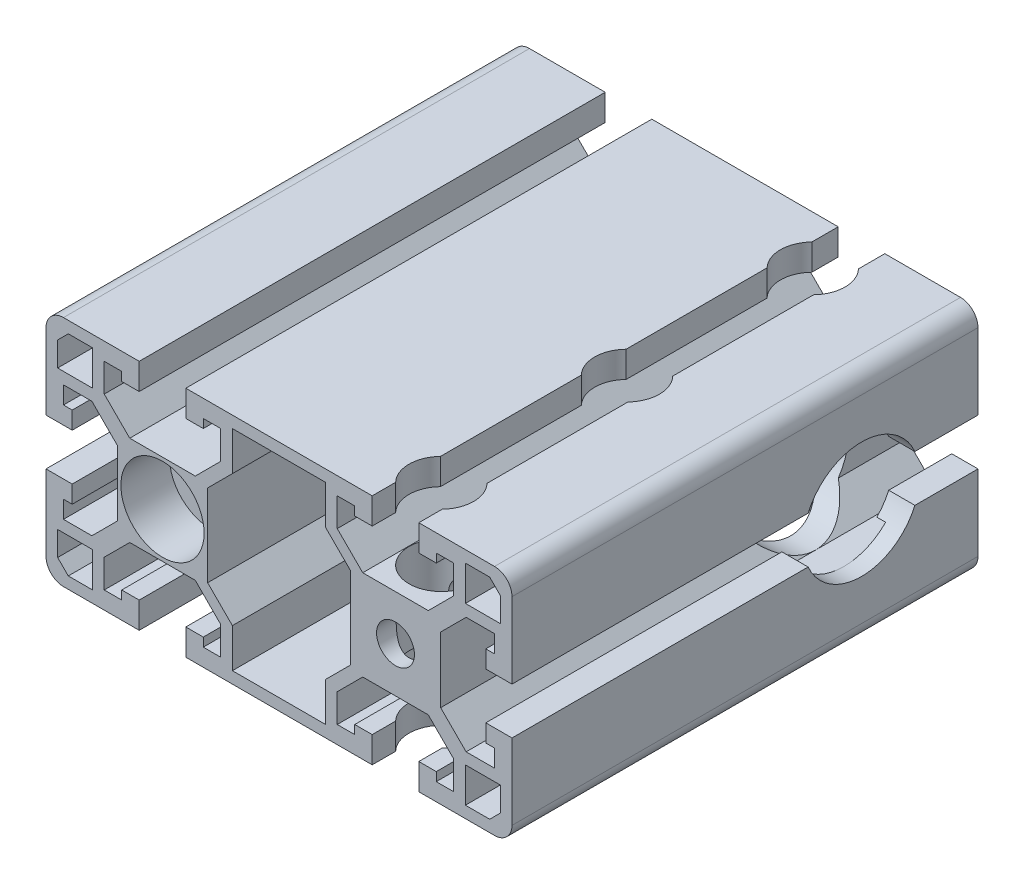
SolidWorks part; units mm, degrees
material "6061 Aluminum Alloy"
ref_plane "Front Plane" through (0, 0, 0) normal (0, 0, 1) x (1, 0, 0)
ref_plane "Top Plane" through (0, 0, 0) normal (0, 1, 0) x (1, 0, 0)
ref_plane "Right Plane" through (0, 0, 0) normal (1, 0, 0) x (0, 0, -1)
ref_plane "Plane1"
sketch "Sketch1" plane through (0, 0, 0) normal (0, 0, 1) x (1, 0, 0)
  line L0 (-24, 24) -> (-24, 37)
  line L1 (-21, 40) -> (-8, 40)
  line L2 (-8, 40) -> (-8, 35.5)
  line L3 (-8, 35.5) -> (-11, 35.5)
  line L4 (-11, 35.5) -> (-11, 37)
  line L5 (-11, 37) -> (-14, 37)
  line L6 (-14, 37) -> (-14, 32.125)
  line L7 (-14, 32.125) -> (-9.625, 27.75)
  line L8 (-9.625, 27.75) -> (1.625, 27.75)
  line L9 (1.625, 27.75) -> (6, 32.125)
  line L10 (6, 32.125) -> (6, 37)
  line L11 (6, 37) -> (3, 37)
  line L12 (3, 37) -> (3, 35.5)
  line L13 (3, 35.5) -> (0, 35.5)
  line L14 (0, 35.5) -> (0, 40)
  line L15 (0, 40) -> (32, 40)
  line L16 (32, 40) -> (32, 35.5)
  line L17 (32, 35.5) -> (29, 35.5)
  line L18 (29, 35.5) -> (29, 37)
  line L19 (29, 37) -> (26, 37)
  line L20 (26, 37) -> (26, 32.125)
  line L21 (26, 32.125) -> (30.375, 27.75)
  line L22 (30.375, 27.75) -> (41.625, 27.75)
  line L23 (41.625, 27.75) -> (46, 32.125)
  line L24 (46, 32.125) -> (46, 37)
  line L25 (46, 37) -> (43, 37)
  line L26 (43, 37) -> (43, 35.5)
  line L27 (43, 35.5) -> (40, 35.5)
  line L28 (40, 35.5) -> (40, 40)
  line L29 (40, 40) -> (53, 40)
  line L30 (56, 37) -> (56, 24)
  line L31 (56, 24) -> (51.5, 24)
  line L32 (51.5, 24) -> (51.5, 27)
  line L33 (51.5, 27) -> (53, 27)
  line L34 (53, 27) -> (53, 30)
  line L35 (53, 30) -> (48.125, 30)
  line L36 (48.125, 30) -> (43.75, 25.625)
  line L37 (43.75, 25.625) -> (43.75, 14.375)
  line L38 (43.75, 14.375) -> (48.125, 10)
  line L39 (48.125, 10) -> (53, 10)
  line L40 (53, 10) -> (53, 13)
  line L41 (53, 13) -> (51.5, 13)
  line L42 (51.5, 13) -> (51.5, 16)
  line L43 (51.5, 16) -> (56, 16)
  line L44 (56, 16) -> (56, 3)
  line L45 (53, 0) -> (40, 0)
  line L46 (40, 0) -> (40, 4.5)
  line L47 (40, 4.5) -> (43, 4.5)
  line L48 (43, 4.5) -> (43, 3)
  line L49 (43, 3) -> (46, 3)
  line L50 (46, 3) -> (46, 7.875)
  line L51 (46, 7.875) -> (41.625, 12.25)
  line L52 (41.625, 12.25) -> (30.375, 12.25)
  line L53 (30.375, 12.25) -> (26, 7.875)
  line L54 (26, 7.875) -> (26, 3)
  line L55 (26, 3) -> (29, 3)
  line L56 (29, 3) -> (29, 4.5)
  line L57 (29, 4.5) -> (32, 4.5)
  line L58 (32, 4.5) -> (32, 0)
  line L59 (32, 0) -> (0, 0)
  line L60 (0, 0) -> (0, 4.5)
  line L61 (0, 4.5) -> (3, 4.5)
  line L62 (3, 4.5) -> (3, 3)
  line L63 (3, 3) -> (6, 3)
  line L64 (6, 3) -> (6, 7.875)
  line L65 (6, 7.875) -> (1.625, 12.25)
  line L66 (1.625, 12.25) -> (-9.625, 12.25)
  line L67 (-9.625, 12.25) -> (-14, 7.875)
  line L68 (-14, 7.875) -> (-14, 3)
  line L69 (-14, 3) -> (-11, 3)
  line L70 (-11, 3) -> (-11, 4.5)
  line L71 (-11, 4.5) -> (-8, 4.5)
  line L72 (-8, 4.5) -> (-8, 0)
  line L73 (-8, 0) -> (-21, 0)
  line L74 (-24, 3) -> (-24, 16)
  line L75 (-24, 16) -> (-19.5, 16)
  line L76 (-19.5, 16) -> (-19.5, 13)
  line L77 (-19.5, 13) -> (-21, 13)
  line L78 (-21, 13) -> (-21, 10)
  line L79 (-21, 10) -> (-16.125, 10)
  line L80 (-16.125, 10) -> (-11.75, 14.375)
  line L81 (-11.75, 14.375) -> (-11.75, 25.625)
  line L82 (-11.75, 25.625) -> (-16.125, 30)
  line L83 (-16.125, 30) -> (-21, 30)
  line L84 (-21, 30) -> (-21, 27)
  line L85 (-21, 27) -> (-19.5, 27)
  line L86 (-19.5, 27) -> (-19.5, 24)
  line L87 (-19.5, 24) -> (-24, 24)
  line L88 (48, 2) -> (48, 8)
  line L89 (48, 8) -> (54, 8)
  line L90 (54, 8) -> (54, 3.8284)
  line L91 (54, 3.8284) -> (52.1716, 2)
  line L92 (52.1716, 2) -> (48, 2)
  line L93 (54, 32) -> (48, 32)
  line L94 (48, 32) -> (48, 38)
  line L95 (48, 38) -> (52.1716, 38)
  line L96 (52.1716, 38) -> (54, 36.1716)
  line L97 (54, 36.1716) -> (54, 32)
  line L98 (-16, 32) -> (-22, 32)
  line L99 (-22, 32) -> (-22, 36.1716)
  line L100 (-22, 36.1716) -> (-20.1716, 38)
  line L101 (-20.1716, 38) -> (-16, 38)
  line L102 (-16, 38) -> (-16, 32)
  line L103 (-22, 8) -> (-16, 8)
  line L104 (-16, 8) -> (-16, 2)
  line L105 (-16, 2) -> (-20.1716, 2)
  line L106 (-20.1716, 2) -> (-22, 3.8284)
  line L107 (-22, 3.8284) -> (-22, 8)
  line L108 (24, 31.2966) -> (28.25, 27.0466)
  line L109 (28.25, 27.0466) -> (28.25, 12.9534)
  line L110 (28.25, 12.9534) -> (24, 8.7034)
  line L111 (24, 8.7034) -> (24, 2)
  line L112 (24, 2) -> (8, 2)
  line L113 (8, 2) -> (8, 8.7034)
  line L114 (8, 8.7034) -> (3.75, 12.9534)
  line L115 (3.75, 12.9534) -> (3.75, 27.0466)
  line L116 (3.75, 27.0466) -> (8, 31.2966)
  line L117 (8, 31.2966) -> (8, 38)
  line L118 (8, 38) -> (24, 38)
  line L119 (24, 38) -> (24, 31.2966)
  arc A0 (-21, 40) -> (-24, 37) centre (-21, 37) ccw
  arc A1 (56, 37) -> (53, 40) centre (53, 37) ccw
  arc A2 (53, 0) -> (56, 3) centre (53, 3) ccw
  arc A3 (-24, 3) -> (-21, 0) centre (-21, 3) ccw
  circle A4 centre (36, 20) radius 3.25
  circle A5 centre (-4, 20) radius 3.25
  dimension "D1" = 3
  dimension "D2" = 3
  dimension "D3" = 6.5
extrude "Extrusion1" add sketch "Sketch1" along normal mid plane 80 contours L74 A3 L73 L72 L71 L70 L69 L68 L67 L66 L65 L64 L63 L62 L61 L60 L59 L58 L57 L56 L55 L54 L53 L52 L51 L50 L49 L48 L47 L46 L45 A2 L44 L43 L42 L41 L40 L39 L38 L37 L36 L35 L34 L33 L32 L31 L30 A1 L29 L28 L27
hole_wizard "Ø20.0 (20) Diameter Hole1" positions "Sketch3" profile "Sketch4" hole size "Ø20.0" standard "Macron Ansi Metric"
sketch "Sketch3" plane through (56, 0, 0) normal (1, 0, 0) x (0, 0, -1)
  line L0 (40, 37) -> (40, 24) construction
  line L1 (-40, 40) -> (40, 40) construction
  point P0 (20, 20)
  dimension "D1" = 20
  dimension "D2" = 20
sketch "Sketch4" plane through (56, 20, -20) normal (0, 1, 0) x (0, 0, -1)
  line L0 (0, 0) -> (0, 16)
  line L1 (0, 16) -> (10, 16)
  line L2 (10, 16) -> (10, 0)
  line L5 (10, 0) -> (0, 0)
  line L10 (0, 16) -> (-10, 16) construction
  line L11 (0, -6.35) -> (0, 107.95) construction
  dimension "Hole Dia." = 20
  dimension "Hole Depth" = 16
  dimension "Drill Angle" = 180
hole_wizard "CBORE for 1/4 Binding Head Machine Screw1" positions "Sketch6" profile "Sketch7" counterbore size "1/4" standard "Macron Ansi Inch" end condition through all
sketch "Sketch6" plane through (0, 0, 40) normal (0, 0, 1) x (1, 0, 0)
  point P0 (-4, 20)
sketch "Sketch7" plane through (-4, 20, 40) normal (1, 0, 0) x (0, -1, 0)
  line L0 (0, 0) -> (0, 80)
  line L1 (0, 80) -> (4.1656, 80)
  line L3 (4.1656, 80) -> (4.1656, 8.3312)
  line L4 (4.1656, 8.3312) -> (7.1437, 8.3312)
  line L5 (7.1437, 8.3312) -> (7.1438, 0)
  line L7 (7.1438, 0) -> (0, 0)
  line L11 (0, -6.35) -> (0, 107.95) construction
  dimension "Thru Hole Dia." = 8.3312
  dimension "Thru Hole Depth" = 80
  dimension "C'Bore Dia." = 14.2875
  dimension "C'Bore Depth" = 8.3312
hole_wizard "Ø11.0 (11) Diameter Hole1" positions "Sketch9" profile "Sketch10" hole size "Ø11.0" standard "Ansi Metric" end condition through all
sketch "Sketch9" plane through (0, 40, 0) normal (0, 1, 0) x (-1, 0, 0)
  line L0 (-56, 40) -> (-56, -40) construction
  line L1 (-40, -40) -> (-53, -40) construction
  point P0 (-36, -31.63)
  point P14 (-36, 0.25)
  point P15 (-36, 32.13)
  dimension "D1" = 20
  dimension "D2" = 8.37
  dimension "D3" = 3
sketch "Sketch10" plane through (36, 40, -31.63) normal (1, 0, 0) x (0, 0, 1)
  line L0 (0, 0) -> (0, 40)
  line L1 (0, 40) -> (5.55, 40)
  line L2 (5.55, 40) -> (5.55, 0)
  line L5 (5.55, 0) -> (0, 0)
  line L11 (0, -6.35) -> (0, 107.95) construction
  dimension "Thru Hole Dia." = 11.1
  dimension "Thru Hole Depth" = 40
